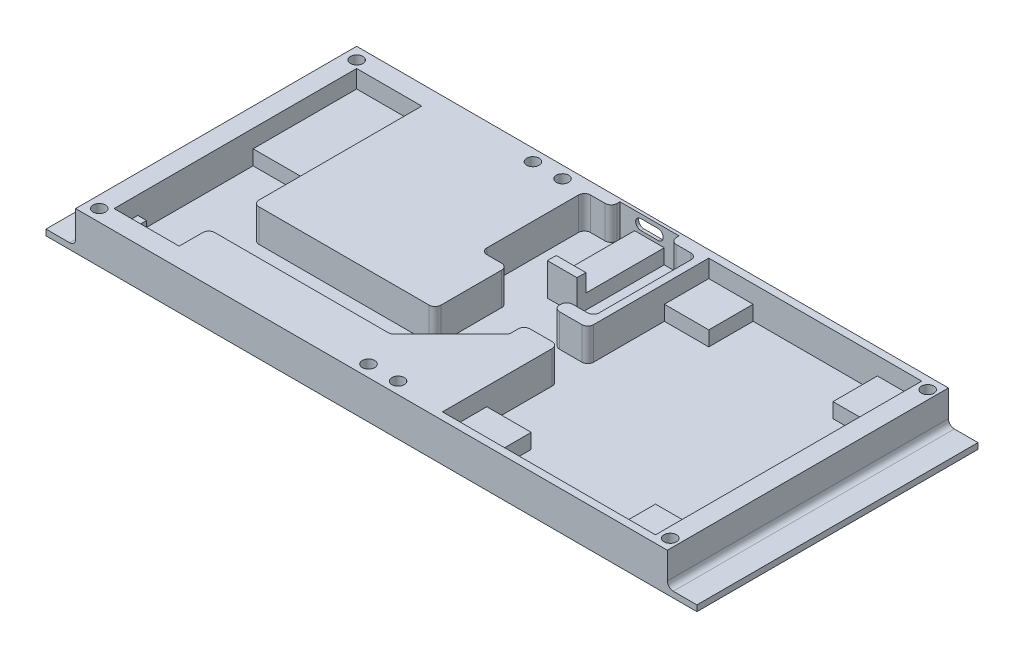
SolidWorks part; units mm, degrees
ref_plane "Front Plane" through (0, 0, 0) normal (0, 0, 1) x (1, 0, 0)
ref_plane "Top Plane" through (0, 0, 0) normal (0, 1, 0) x (1, 0, 0)
ref_plane "Right Plane" through (0, 0, 0) normal (1, 0, 0) x (0, 0, -1)
sketch "Sketch2" plane through (0, 0, 0) normal (0, 1, 0) x (1, 0, 0)
  line L0 (0, 0) -> (-50000, 0) construction
  line L1 (-100, 47.5) -> (100, 47.5)
  line L2 (-100, 47.5) -> (-100, -47.5)
  line L3 (-100, -47.5) -> (100, -47.5)
  line L4 (100, 47.5) -> (100, -47.5)
  line L5 (-100, 47.5) -> (100, -47.5) construction
  line L6 (-100, -47.5) -> (100, 47.5) construction
  line L7 (21.5, 45) -> (93.5, 45)
  line L8 (21.5, 45) -> (21.5, -45)
  line L9 (21.5, -45) -> (93.5, -45)
  line L10 (93.5, 45) -> (93.5, -45)
  line L11 (21.5, 45) -> (93.5, -45) construction
  line L12 (21.5, -45) -> (93.5, 45) construction
  line L13 (-93.5, 41) -> (-71.5, 41)
  line L14 (-93.5, 41) -> (-93.5, -41)
  line L15 (-93.5, -41) -> (-71.5, -41)
  line L16 (-71.5, 41) -> (-71.5, -41)
  line L17 (-93.5, 41) -> (-71.5, -41) construction
  line L18 (-93.5, -41) -> (-71.5, 41) construction
  line L19 (0, 0) -> (0, -50000) construction
  line L20 (-10, 46.5) -> (10, 46.5)
  line L21 (-10, 46.5) -> (-10, 22.5)
  line L22 (-10, 22.5) -> (10, 22.5)
  line L23 (10, 46.5) -> (10, 22.5)
  line L24 (-10, 46.5) -> (10, 22.5) construction
  line L25 (-10, 22.5) -> (10, 46.5) construction
  line L26 (-10, -31) -> (10, -11)
  line L27 (-71.5, -16) -> (-10, -16)
  line L28 (-71.5, -16) -> (-71.5, -31)
  line L29 (-71.5, -31) -> (-10, -31)
  line L30 (-10, -16) -> (-10, -31)
  line L31 (21.5, 4.0911) -> (10, 4.0911)
  line L32 (21.5, 4.0911) -> (21.5, -5.9089)
  line L33 (21.5, -5.9089) -> (10, -5.9089)
  line L34 (10, 4.0911) -> (10, -5.9089)
  line L35 (10, 22.5) -> (10, -11)
  line L37 (-10, 22.5) -> (-10, -31)
  line L46 (-10, 43.5) -> (-19, 43.5)
  line L47 (-10, 43.5) -> (-10, 8.5)
  line L48 (-10, 8.5) -> (-19, 8.5)
  line L49 (-19, 43.5) -> (-19, 8.5)
  line L50 (10, 43.5) -> (19, 43.5)
  line L51 (10, 43.5) -> (10, 8.5)
  line L52 (10, 8.5) -> (19, 8.5)
  line L53 (19, 43.5) -> (19, 8.5)
  point P0 (0, 0)
  point P6 (57.5, 0)
  point P12 (-82.5, 0)
  point P20 (0, 34.5)
  dimension "D1" = 200
  dimension "D2" = 90
  dimension "D3" = 72
  dimension "D4" = 95
  dimension "D5" = 82
  dimension "D6" = 22
  dimension "D7" = 6.5
  dimension "D8" = 6.5
  dimension "D9" = 20
  dimension "D10" = 24
  dimension "D11" = 1
  dimension "D12" = 15
  dimension "D13" = 10
  dimension "D14" = 10
  dimension "D15" = 35
  dimension "D16" = 9
  dimension "D17" = 3
extrude "Boss-Extrude1" add sketch "Sketch2" along normal blind 11 contours L4 L1 L2 L3 L37 L21 L20 L23 L35 L31 L8 L7 L10 L9 L33 L26 L29 L16 L15 L14 L13 L27
sketch "Sketch3" plane through (0, 0, 0) normal (0, -1, 0) x (1, 0, 0)
  line L1 (-100, 47.5) -> (100, 47.5)
  line L2 (-100, 47.5) -> (-100, -47.5)
  line L3 (-100, -47.5) -> (100, -47.5)
  line L4 (100, 47.5) -> (100, -47.5)
extrude "Boss-Extrude2" add sketch "Sketch3" along normal blind 2
sketch "Sketch4" plane through (0, 0, 0) normal (0, 1, 0) x (1, 0, 0)
  line L0 (-71.5, 41) -> (-71.5, -16) construction
  line L1 (-93.5, 41) -> (-71.5, 41)
  line L2 (-93.5, 41) -> (-93.5, 6)
  line L3 (-93.5, 6) -> (-71.5, 6)
  line L4 (-71.5, 41) -> (-71.5, 6)
  line L5 (-5.0462, 46.5) -> (4.9538, 46.5)
  line L6 (-93.5, -41) -> (-90.5, -41)
  line L7 (-93.5, -41) -> (-93.5, -33)
  line L8 (-93.5, -33) -> (-90.5, -33)
  line L9 (-90.5, -41) -> (-90.5, -33)
  line L10 (21.5, 45) -> (36.5, 45)
  line L11 (21.5, 45) -> (21.5, 30)
  line L12 (21.5, 30) -> (36.5, 30)
  line L13 (36.5, 45) -> (36.5, 30)
  line L14 (93.5, 45) -> (78.5, 45)
  line L15 (93.5, 45) -> (93.5, 30)
  line L16 (93.5, 30) -> (78.5, 30)
  line L17 (78.5, 45) -> (78.5, 30)
  line L18 (93.5, -45) -> (78.5, -45)
  line L19 (93.5, -45) -> (93.5, -30)
  line L20 (93.5, -30) -> (78.5, -30)
  line L21 (78.5, -45) -> (78.5, -30)
  line L22 (21.5, -45) -> (36.5, -45)
  line L23 (21.5, -45) -> (21.5, -30)
  line L24 (21.5, -30) -> (36.5, -30)
  line L25 (36.5, -45) -> (36.5, -30)
  line L26 (-10, 46.5) -> (10, 46.5) construction
  line L27 (4.9538, 46.5) -> (4.9538, 20)
  line L28 (4.9538, 20) -> (-5.0462, 20)
  line L29 (-5.0462, 20) -> (-5.0462, 46.5)
  point P37 (-0.0462, 46.5)
  dimension "D1" = 35
  dimension "D2" = 8
  dimension "D3" = 3
  dimension "D4" = 15
  dimension "D5" = 15
  dimension "D6" = 15
  dimension "D7" = 15
  dimension "D8" = 10
  dimension "D9" = 26.5
extrude "Boss-Extrude3" add sketch "Sketch4" along normal blind 5
sketch "Sketch5" plane through (0, 0, -46.5) normal (0, 0, 1) x (1, 0, 0)
  line L0 (4.9538, 5) -> (-5.0462, 5) construction
  line L5 (-2.9462, 7.85) -> (2.8538, 7.85) construction
  line L6 (-2.9462, 9.6) -> (2.8538, 9.6)
  line L7 (-0.0462, 5) -> (-0.0462, 7.85)
  line L8 (-2.9462, 6.1) -> (2.8538, 6.1)
  arc A0 (-2.9462, 9.6) -> (-2.9462, 6.1) centre (-2.9462, 7.85) ccw
  arc A1 (2.8538, 6.1) -> (2.8538, 9.6) centre (2.8538, 7.85) ccw
  point P0 (-0.0462, 7.85)
  point P3 (-0.0462, 7.85)
  dimension "D2" = 9.3
  dimension "D1" = 3.5
  dimension "D3" = 1.1
extrude "Cut-Extrude1" cut sketch "Sketch5" against normal blind 7
sketch "Sketch7" plane through (0, -2, 0) normal (0, -1, 0) x (1, 0, 0)
  line L0 (-100, -47.5) -> (100, -47.5) construction
  line L1 (-110, 47.5) -> (110, 47.5)
  line L2 (-110, 47.5) -> (-110, -47.5)
  line L3 (-110, -47.5) -> (110, -47.5)
  line L4 (110, 47.5) -> (110, -47.5)
  line L5 (-110, 47.5) -> (110, -47.5) construction
  line L6 (-110, -47.5) -> (110, 47.5) construction
  line L7 (-100, 47.5) -> (-100, -47.5) construction
  point P0 (0, 0)
  dimension "D1" = 10
sketch "Sketch9" plane through (0, 0, 0) normal (0, 1, 0) x (1, 0, 0)
  line L0 (4.9538, 20) -> (4.9538, 46.5) construction
  line L1 (-5.0462, 20) -> (4.9538, 20)
  line L2 (-5.0462, 20) -> (-5.0462, 17)
  line L3 (-5.0462, 17) -> (4.9538, 17)
  line L4 (4.9538, 20) -> (4.9538, 17)
  dimension "D1" = 3
ref_plane "Plane1" through (4.9538, 0, -20) normal (0, 0, -1) x (-1, 0, 0)
extrude "Boss-Extrude4" add sketch "Sketch9" along normal up to surface (11 mm away) up to face at (0, 11, 0)
extrude "Boss-Extrude5" add sketch "Sketch7" against normal blind 2
fillet "Fillet1" radius 2 2 edges at (-100, 0, 0) (100, 0, 0)
fillet "Fillet2" radius 2 17 edges at (-10, 5.5, 31) (21.5, 5.5, 5.9089) (21.5, 5.5, -4.0911) (10, 5.5, -4.0911) (10, 5.5, 5.9089) (10, 5.5, 11) (-71.5, 5.5, 31) (-71.5, 5.5, 16) (-10, 5.5, -8.5) (-19, 5.5, -8.5) (19, 5.5, -8.5) (10, 5.5, -8.5) (-19, 5.5, -43.5) (-10, 5.5, -43.5) (19, 5.5, -43.5) (10, 5.5, -43.5) (-10, 5.5, 16)
sketch "Sketch10" plane through (0, 11, 0) normal (0, 1, 0) x (1, 0, 0)
  line L0 (-100, 47.5) -> (-100, -47.5) construction
  line L1 (-100, 47.5) -> (100, 47.5) construction
  line L2 (-100, -47.5) -> (100, -47.5) construction
  line L3 (100, 47.5) -> (100, -47.5) construction
  line L4 (-7.0711, 31.4289) -> (-31.4289, 31.4289) construction
  line L5 (0, 24.3579) -> (0, 0) construction
  line L6 (-31.4289, 31.4289) -> (0, 0)
  line L7 (0, 0) -> (0, -47.5)
  line L8 (-31.4289, 31.4289) -> (-31.4289, 47.5)
  line L9 (-100, 0) -> (0, 0) construction
  line L10 (-100, 47.5) -> (100, 47.5)
  line L11 (-100, 47.5) -> (-100, -47.5)
  line L12 (-100, -47.5) -> (100, -47.5)
  line L13 (100, 47.5) -> (100, -47.5)
  line L14 (0, 24.3579) -> (-7.0711, 31.4289)
  line L15 (-7.0711, 31.4289) -> (0, 38.5)
  line L16 (0, 38.5) -> (7.0711, 31.4289)
  line L17 (7.0711, 31.4289) -> (0, 24.3579)
  line L18 (0, 38.5) -> (0, 47.5) construction
  line L19 (-5, -43.5) -> (5, -43.5) construction
  line L20 (-36.4289, 43.5) -> (-26.4289, 43.5) construction
  circle A0 centre (-96, 43.5) radius 2.1
  circle A1 centre (-96, -43.5) radius 2.1
  circle A2 centre (97, -43.5) radius 2.1
  circle A3 centre (97, 43.5) radius 2.1
  circle A4 centre (5, -43.5) radius 2.1
  circle A5 centre (-5, -43.5) radius 2.1
  circle A6 centre (-26.4289, 43.5) radius 2.1
  circle A7 centre (-36.4289, 43.5) radius 2.1
  point P23 (-100, 0)
  point P29 (0, -47.5)
  point P36 (0, -43.5)
  point P39 (-31.4289, 43.5)
  dimension "D1" = 4.2
  dimension "D13" = 4.2
  dimension "D2" = 4
  dimension "D3" = 4
  dimension "D4" = 4
  dimension "D5" = 4
  dimension "D6" = 3
  dimension "D7" = 4
  dimension "D8" = 3
  dimension "D9" = 4
  dimension "D10" = 10
  dimension "D11" = 9
  dimension "D12" = 10
  dimension "D14" = 4
extrude "Cut-Extrude2" cut sketch "Sketch10" against normal blind 6 contours A1 | A5 | A4 | A2 | A3 | A6 | A7 | A0
